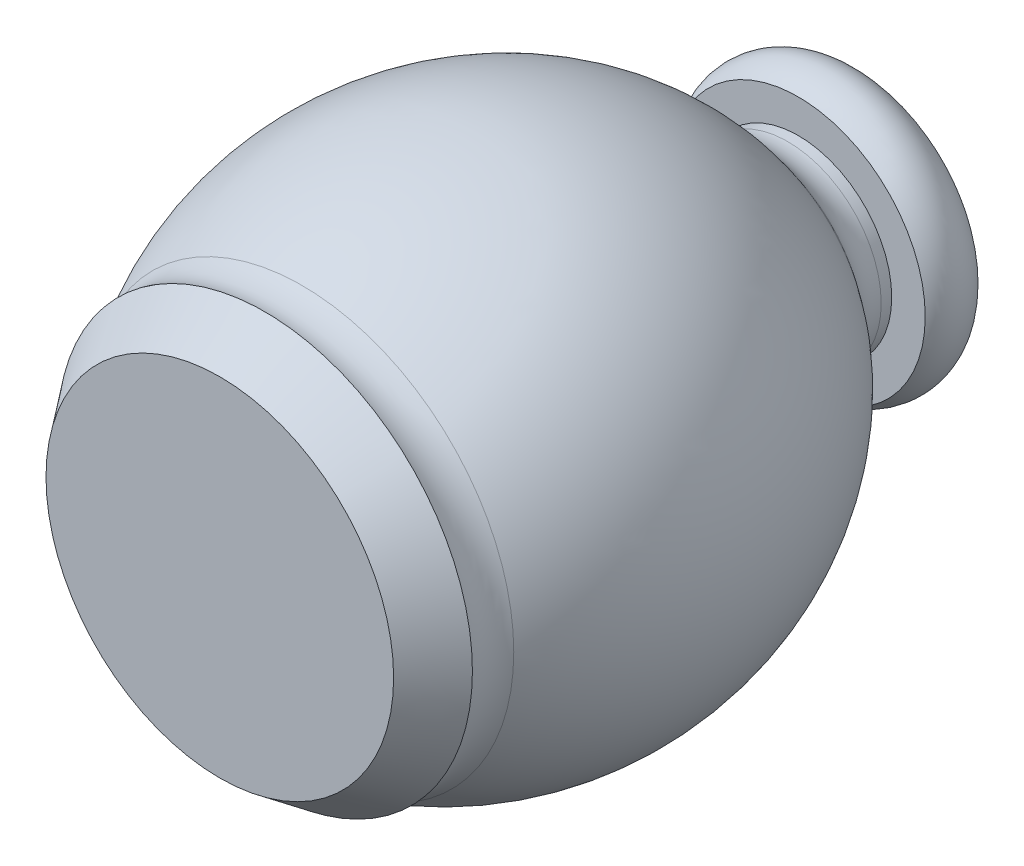
SolidWorks part; units mm, degrees
ref_plane "Front Plane" through (0, 0, 0) normal (0, 0, 1) x (1, 0, 0)
ref_plane "Top Plane" through (0, 0, 0) normal (0, 1, 0) x (1, 0, 0)
ref_plane "Right Plane" through (0, 0, 0) normal (1, 0, 0) x (0, 0, -1)
sketch "Sketch1" plane through (0, 0, 0) normal (0, 1, 0) x (1, 0, 0)
  line L0 (0, 0) -> (0, 84.7765) construction
  line L1 (-30.2051, 3.2101) -> (-27.5885, 0)
  line L2 (-27.5885, 0) -> (0, 0)
  line L3 (-18.5557, 77.4382) -> (-15.8883, 79.4323)
  line L4 (-11.8758, 87.4416) -> (-11.8758, 92.1148)
  line L5 (-11.8758, 92.1148) -> (-18.5557, 92.1148)
  line L6 (0, -3) -> (-27.6769, -3)
  line L7 (-16.5512, 96.506) -> (-11.8758, 96.506)
  line L8 (-33.0441, 4.1795) -> (-27.6769, -3)
  line L9 (-20.352, 79.841) -> (-17.6845, 81.8351)
  line L10 (-14.8758, 87.4416) -> (-14.8758, 89.1148)
  line L11 (-14.8758, 89.1148) -> (-20.2103, 89.1148)
  line L12 (-17.006, 99.506) -> (-11.8758, 99.506)
  line L13 (-11.8758, 96.506) -> (-11.8758, 99.506)
  line L14 (0, 0) -> (0, -3)
  line L15 (-31.3012, 0) -> (-30.2051, 3.2101) construction
  line L16 (-35.4957, -3) -> (-33.0441, 4.1795) construction
  line L17 (0, 0) -> (-31.3012, 0) construction
  line L19 (0, -3) -> (-35.4957, -3) construction
  arc A0 (-31.1461, 11.673) -> (-18.5557, 77.4382) centre (11.1836, 37.657) cw
  arc A1 (-11.8758, 87.4416) -> (-15.8883, 79.4323) centre (-21.8758, 87.4416) cw
  arc A2 (-31.1461, 11.673) -> (-30.2051, 3.2101) centre (-39.6686, 6.4415) cw
  arc A3 (-18.5557, 92.1148) -> (-16.5512, 96.506) centre (-15.3578, 93.3081) cw
  arc A4 (-33.7029, 10.1035) -> (-33.0441, 4.1795) centre (-39.6686, 6.4415) cw
  arc A5 (-33.7029, 10.1035) -> (-20.352, 79.841) centre (11.1836, 37.657) cw
  arc A6 (-14.8758, 87.4416) -> (-17.6845, 81.8351) centre (-21.8758, 87.4416) cw
  arc A7 (-20.2103, 89.1148) -> (-17.006, 99.506) centre (-15.3578, 93.3081) cw
  dimension "D1" = 10
  dimension "D2" = 10
  dimension "D3" = 3
revolve "Revolve2" add sketch "Sketch1" angle 360 about L0
